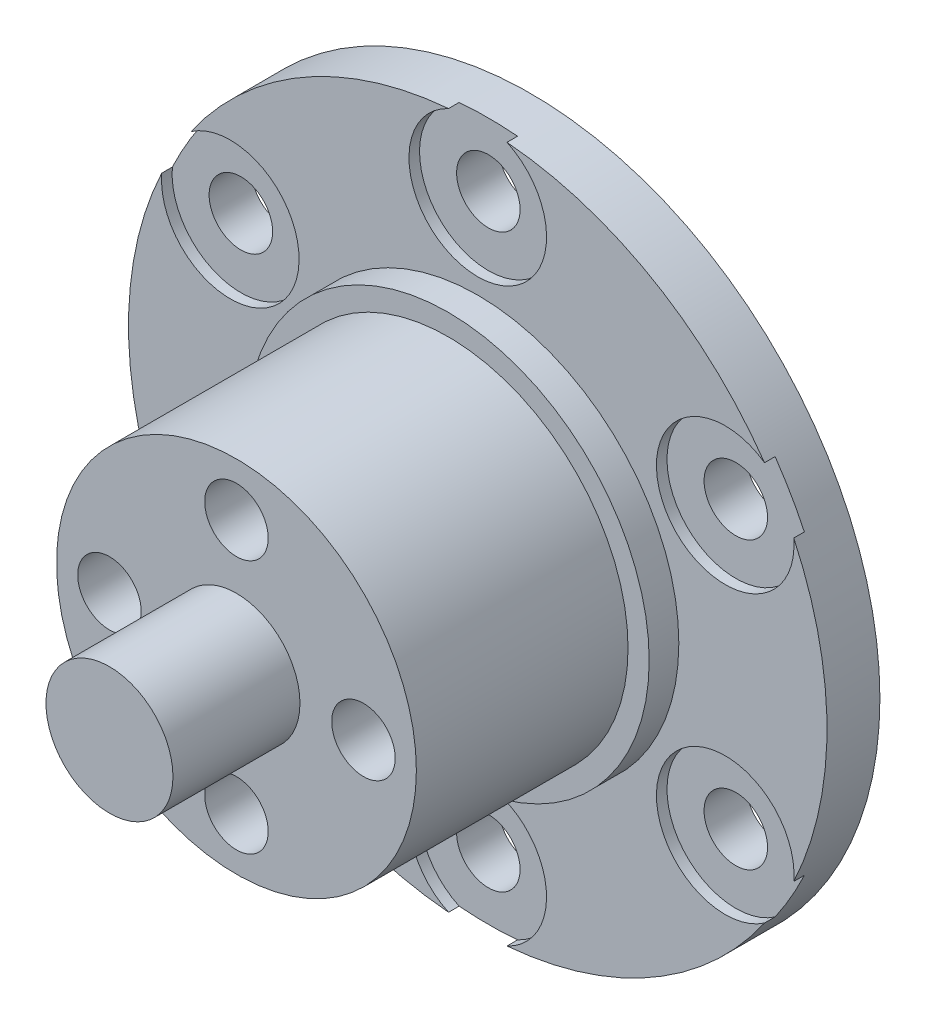
SolidWorks part; units mm, degrees
material "6061 合金"
ref_plane "前视基准面" through (0, 0, 0) normal (0, 0, 1) x (1, 0, 0)
ref_plane "上视基准面" through (0, 0, 0) normal (0, 1, 0) x (1, 0, 0)
ref_plane "右视基准面" through (0, 0, 0) normal (1, 0, 0) x (0, 0, -1)
sketch "草图1" plane through (0, 0, 0) normal (0, 0, 1) x (1, 0, 0)
  circle A0 centre (0, 0) radius 13.5 construction
  circle A1 centre (0, 0) radius 16.5
  dimension "D1" = 27
  dimension "D2" = 3
extrude "凸台-拉伸1" add sketch "草图1" along normal blind 2.5
sketch "草图2" plane through (0, 0, 2.5) normal (0, 0, 1) x (1, 0, 0)
  circle A0 centre (0, 0) radius 9.5
  dimension "D1" = 19
extrude "凸台-拉伸2" add sketch "草图2" along normal blind 1.4
sketch "草图3" plane through (0, 0, 2.5) normal (0, 0, 1) x (1, 0, 0)
  circle A0 centre (0, 0) radius 13.5 construction
  circle A1 centre (0, 13.5) radius 1.5
  circle A2 centre (11.6913, 6.75) radius 1.5
  circle A3 centre (11.6913, -6.75) radius 1.5
  circle A4 centre (0, -13.5) radius 1.5
  circle A5 centre (-11.6913, -6.75) radius 1.5
  circle A6 centre (-11.6913, 6.75) radius 1.5
  point P6 (19.6717, -7.608)
  point P7 (0, 0)
  point P17 (0, 0)
  dimension "D1" = 27
  dimension "D2" = 3
  dimension "D3" = 6
extrude "切除-拉伸1" cut sketch "草图3" against normal blind 3
sketch "草图4" plane through (0, 0, 3.9) normal (0, 0, 1) x (1, 0, 0)
  circle A0 centre (0, 0) radius 8.5
  dimension "D1" = 17
extrude "凸台-拉伸3" add sketch "草图4" along normal blind 10
sketch "草图5" plane through (0, 0, 13.9) normal (0, 0, 1) x (1, 0, 0)
  circle A0 centre (0, 0) radius 6 construction
  circle A1 centre (0, 0) radius 8.5 construction
  dimension "D1" = 2.5
hole_wizard "M3 螺纹孔1" positions "草图6" profile "草图7" tap size "M3" standard "GB"
sketch "草图6" plane through (0, 0, 13.9) normal (0, 0, 1) x (1, 0, 0)
  line L0 (0, 6) -> (0, 0) construction
  circle A0 centre (0, 0) radius 6 construction
  point P0 (0, 6)
sketch "草图7" plane through (0, 6, 13.9) normal (1, 0, 0) x (0, -1, 0)
  line L0 (0, 0) -> (0, 8.4013)
  line L1 (0, 8.4013) -> (1.5, 7.5)
  line L2 (1.5, 7.5) -> (1.5, 0)
  line L5 (1.5, 0) -> (0, 0)
  line L10 (0, 8.4013) -> (-1.5, 7.5) construction
  line L11 (0, -6.35) -> (0, 107.95) construction
  dimension "螺纹孔钻头直径" = 3
  dimension "螺纹孔钻头深度" = 7.5
  dimension "导头角度" = 118
cosmetic thread "孔螺蚊线1" parameters "D1"=6, "D2"=3
pattern_circular "阵列(圆周)1" count 4 over 360 about axis through (0, 0, 0) along (0, 0, 1) of "M3 螺纹孔1"
cosmetic thread "孔螺蚊线2" parameters "D1"=6, "D2"=3
cosmetic thread "孔螺蚊线3" parameters "D1"=6, "D2"=3
cosmetic thread "孔螺蚊线4" parameters "D1"=6, "D2"=3
sketch "草图8" plane through (0, 0, 13.9) normal (0, 0, 1) x (1, 0, 0)
  circle A0 centre (0, 0) radius 3
  dimension "D1" = 6
extrude "凸台-拉伸4" add sketch "草图8" along normal blind 6
sketch "草图9" plane through (0, 0, 2.5) normal (0, 0, 1) x (1, 0, 0)
  circle A0 centre (0, 13.5) radius 3.25
  circle A1 centre (11.6913, 6.75) radius 3.25
  circle A2 centre (11.6913, -6.75) radius 3.25
  circle A3 centre (0, -13.5) radius 3.25
  circle A4 centre (-11.6913, -6.75) radius 3.25
  circle A5 centre (-11.6913, 6.75) radius 3.25
  point P3 (18.1568, -6.2025)
  point P4 (0, 0)
  point P16 (0, 0)
  dimension "D1" = 6.5
  dimension "D2" = 6
extrude "切除-拉伸2" cut sketch "草图9" against normal blind 0.5
